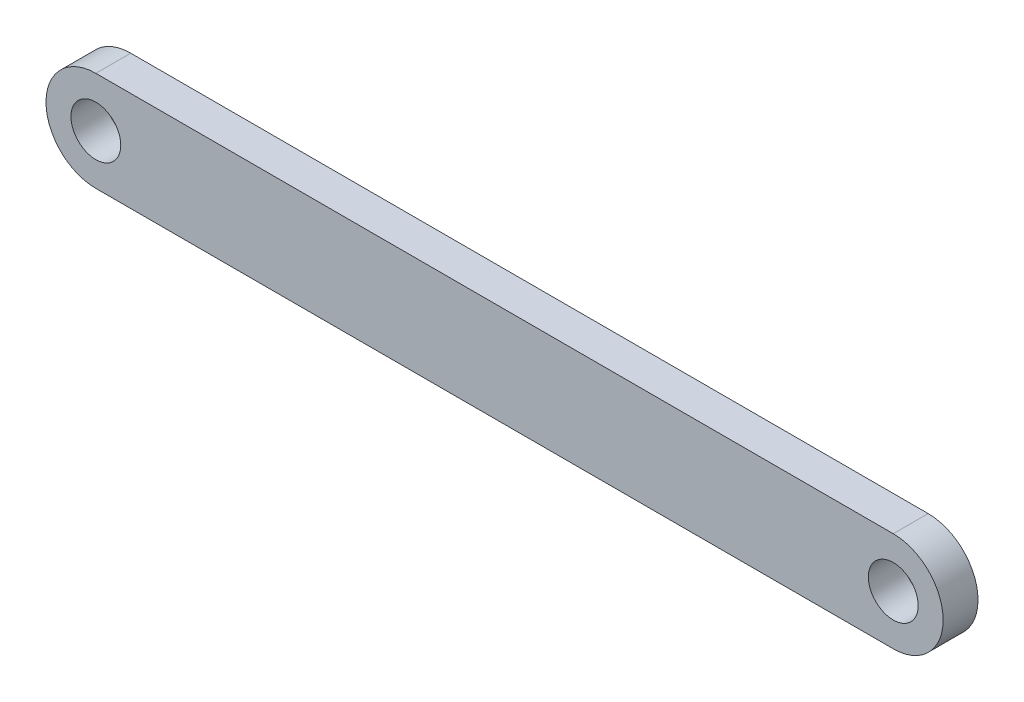
SolidWorks part; units mm, degrees
ref_plane "前视基准面" through (0, 0, 0) normal (0, 0, 1) x (1, 0, 0)
ref_plane "上视基准面" through (0, 0, 0) normal (0, 1, 0) x (1, 0, 0)
ref_plane "右视基准面" through (0, 0, 0) normal (1, 0, 0) x (0, 0, -1)
other "Configuration Table"
sketch "草图1" plane through (0, 0, 0) normal (0, 0, 1) x (1, 0, 0)
  line L0 (0, 10) -> (160, 10)
  line L1 (0, -10) -> (160, -10)
  arc A0 (0, 10) -> (0, -10) centre (0, 0) ccw
  arc A1 (160, -10) -> (160, 10) centre (160, 0) ccw
  circle A2 centre (0, 0) radius 5
  circle A3 centre (160, 0) radius 5
  dimension "D1" = 20
  dimension "D3" = 10
  dimension "D2" = 160
extrude "凸台-拉伸1" add sketch "草图1" along normal blind 7
